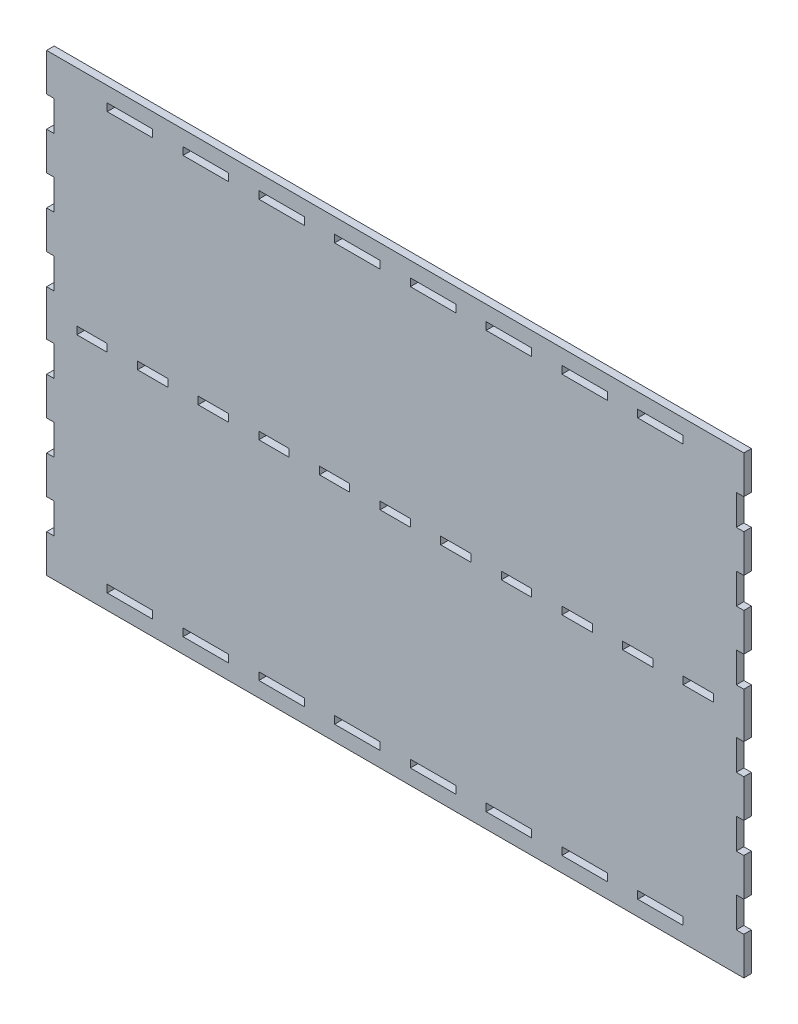
SolidWorks part; units mm, degrees
ref_plane "Front Plane" through (0, 0, 0) normal (0, 0, 1) x (1, 0, 0)
ref_plane "Top Plane" through (0, 0, 0) normal (0, 1, 0) x (1, 0, 0)
ref_plane "Right Plane" through (0, 0, 0) normal (1, 0, 0) x (0, 0, -1)
sketch "Sketch1" plane through (0, 0, 0) normal (0, 0, 1) x (1, 0, 0)
  line L0 (-145.2465, -150.1691) -> (-145.2465, -112.8993) construction
  line L1 (84.7535, -219.7844) -> (-375.2465, -219.7844)
  line L2 (84.7535, -219.7844) -> (84.7535, -194.7844)
  line L3 (84.7535, 80.2156) -> (-375.2465, 80.2156)
  line L4 (-375.2465, -219.7844) -> (-375.2465, -194.7844)
  line L5 (-118.9898, -69.7844) -> (-123.7326, -69.7844) construction
  line L6 (-55.2465, -204.7844) -> (-85.2465, -204.7844)
  line L7 (-105.2465, -209.7844) -> (-135.2465, -209.7844)
  line L8 (-105.2465, -209.7844) -> (-105.2465, -204.7844)
  line L9 (-105.2465, -204.7844) -> (-135.2465, -204.7844)
  line L10 (-135.2465, -209.7844) -> (-135.2465, -204.7844)
  line L11 (-85.2465, -209.7844) -> (-85.2465, -204.7844)
  line L12 (-55.2465, -209.7844) -> (-85.2465, -209.7844)
  line L13 (-55.2465, -209.7844) -> (-55.2465, -204.7844)
  line L14 (-5.2465, -204.7844) -> (-35.2465, -204.7844)
  line L15 (-35.2465, -209.7844) -> (-35.2465, -204.7844)
  line L16 (-5.2465, -209.7844) -> (-35.2465, -209.7844)
  line L17 (-5.2465, -209.7844) -> (-5.2465, -204.7844)
  line L18 (44.7535, -204.7844) -> (14.7535, -204.7844)
  line L19 (14.7535, -209.7844) -> (14.7535, -204.7844)
  line L20 (44.7535, -209.7844) -> (14.7535, -209.7844)
  line L21 (44.7535, -209.7844) -> (44.7535, -204.7844)
  line L22 (-335.2465, -209.7844) -> (-335.2465, -204.7844)
  line L23 (-335.2465, -209.7844) -> (-305.2465, -209.7844)
  line L24 (-305.2465, -209.7844) -> (-305.2465, -204.7844)
  line L25 (-335.2465, -204.7844) -> (-305.2465, -204.7844)
  line L26 (-285.2465, -209.7844) -> (-285.2465, -204.7844)
  line L27 (-285.2465, -209.7844) -> (-255.2465, -209.7844)
  line L28 (-255.2465, -209.7844) -> (-255.2465, -204.7844)
  line L29 (-285.2465, -204.7844) -> (-255.2465, -204.7844)
  line L30 (-235.2465, -209.7844) -> (-235.2465, -204.7844)
  line L31 (-235.2465, -209.7844) -> (-205.2465, -209.7844)
  line L32 (-205.2465, -209.7844) -> (-205.2465, -204.7844)
  line L33 (-155.2465, -209.7844) -> (-155.2465, -204.7844)
  line L34 (-185.2465, -204.7844) -> (-155.2465, -204.7844)
  line L35 (-185.2465, -209.7844) -> (-185.2465, -204.7844)
  line L36 (-185.2465, -209.7844) -> (-155.2465, -209.7844)
  line L37 (-235.2465, -204.7844) -> (-205.2465, -204.7844)
  line L38 (-235.2465, 65.2156) -> (-205.2465, 65.2156)
  line L39 (-185.2465, 70.2156) -> (-155.2465, 70.2156)
  line L40 (-185.2465, 70.2156) -> (-185.2465, 65.2156)
  line L41 (-185.2465, 65.2156) -> (-155.2465, 65.2156)
  line L42 (-155.2465, 70.2156) -> (-155.2465, 65.2156)
  line L43 (-205.2465, 70.2156) -> (-205.2465, 65.2156)
  line L44 (-235.2465, 70.2156) -> (-205.2465, 70.2156)
  line L45 (-235.2465, 70.2156) -> (-235.2465, 65.2156)
  line L46 (-285.2465, 65.2156) -> (-255.2465, 65.2156)
  line L47 (-255.2465, 70.2156) -> (-255.2465, 65.2156)
  line L48 (-285.2465, 70.2156) -> (-255.2465, 70.2156)
  line L49 (-285.2465, 70.2156) -> (-285.2465, 65.2156)
  line L50 (-335.2465, 65.2156) -> (-305.2465, 65.2156)
  line L51 (-305.2465, 70.2156) -> (-305.2465, 65.2156)
  line L52 (-335.2465, 70.2156) -> (-305.2465, 70.2156)
  line L53 (-335.2465, 70.2156) -> (-335.2465, 65.2156)
  line L54 (44.7535, 70.2156) -> (44.7535, 65.2156)
  line L55 (44.7535, 70.2156) -> (14.7535, 70.2156)
  line L56 (14.7535, 70.2156) -> (14.7535, 65.2156)
  line L57 (44.7535, 65.2156) -> (14.7535, 65.2156)
  line L58 (-5.2465, 70.2156) -> (-5.2465, 65.2156)
  line L59 (-5.2465, 70.2156) -> (-35.2465, 70.2156)
  line L60 (-35.2465, 70.2156) -> (-35.2465, 65.2156)
  line L61 (-5.2465, 65.2156) -> (-35.2465, 65.2156)
  line L62 (-55.2465, 70.2156) -> (-55.2465, 65.2156)
  line L63 (-55.2465, 70.2156) -> (-85.2465, 70.2156)
  line L64 (-85.2465, 70.2156) -> (-85.2465, 65.2156)
  line L65 (-135.2465, 70.2156) -> (-135.2465, 65.2156)
  line L66 (-105.2465, 65.2156) -> (-135.2465, 65.2156)
  line L67 (-105.2465, 70.2156) -> (-105.2465, 65.2156)
  line L68 (-105.2465, 70.2156) -> (-135.2465, 70.2156)
  line L69 (-55.2465, 65.2156) -> (-85.2465, 65.2156)
  line L70 (79.7535, 10.2156) -> (84.7535, 10.2156)
  line L71 (79.7535, -34.7844) -> (84.7535, -34.7844)
  line L72 (79.7535, -34.7844) -> (79.7535, -54.7844)
  line L73 (79.7535, -54.7844) -> (84.7535, -54.7844)
  line L76 (79.7535, 10.2156) -> (79.7535, -9.7844)
  line L77 (79.7535, -9.7844) -> (84.7535, -9.7844)
  line L78 (79.7535, 55.2156) -> (84.7535, 55.2156)
  line L80 (79.7535, 55.2156) -> (79.7535, 35.2156)
  line L81 (79.7535, 35.2156) -> (84.7535, 35.2156)
  line L82 (79.7535, -174.7844) -> (84.7535, -174.7844)
  line L83 (79.7535, -194.7844) -> (79.7535, -174.7844)
  line L85 (79.7535, -194.7844) -> (84.7535, -194.7844)
  line L86 (79.7535, -129.7844) -> (84.7535, -129.7844)
  line L87 (79.7535, -149.7844) -> (79.7535, -129.7844)
  line L90 (79.7535, -84.7844) -> (84.7535, -84.7844)
  line L91 (79.7535, -104.7844) -> (79.7535, -84.7844)
  line L92 (79.7535, -104.7844) -> (84.7535, -104.7844)
  line L93 (79.7535, -149.7844) -> (84.7535, -149.7844)
  line L94 (-370.2465, -149.7844) -> (-375.2465, -149.7844)
  line L95 (-370.2465, -104.7844) -> (-375.2465, -104.7844)
  line L96 (-370.2465, -104.7844) -> (-370.2465, -84.7844)
  line L97 (-370.2465, -84.7844) -> (-375.2465, -84.7844)
  line L100 (-370.2465, -149.7844) -> (-370.2465, -129.7844)
  line L101 (-370.2465, -129.7844) -> (-375.2465, -129.7844)
  line L102 (-370.2465, -194.7844) -> (-375.2465, -194.7844)
  line L104 (-370.2465, -194.7844) -> (-370.2465, -174.7844)
  line L105 (-370.2465, -174.7844) -> (-375.2465, -174.7844)
  line L106 (-370.2465, 35.2156) -> (-375.2465, 35.2156)
  line L107 (-370.2465, 55.2156) -> (-370.2465, 35.2156)
  line L109 (-370.2465, 55.2156) -> (-375.2465, 55.2156)
  line L110 (-370.2465, -9.7844) -> (-375.2465, -9.7844)
  line L111 (-370.2465, 10.2156) -> (-370.2465, -9.7844)
  line L114 (-370.2465, -54.7844) -> (-375.2465, -54.7844)
  line L115 (-370.2465, -34.7844) -> (-370.2465, -54.7844)
  line L116 (-370.2465, -34.7844) -> (-375.2465, -34.7844)
  line L117 (-370.2465, 10.2156) -> (-375.2465, 10.2156)
  line L118 (84.7535, -34.7844) -> (84.7535, -9.7844)
  line L119 (84.7535, 10.2156) -> (84.7535, 35.2156)
  line L120 (84.7535, 55.2156) -> (84.7535, 80.2156)
  line L121 (84.7535, -174.7844) -> (84.7535, -149.7844)
  line L122 (84.7535, -129.7844) -> (84.7535, -104.7844)
  line L123 (84.7535, -84.7844) -> (84.7535, -54.7844)
  line L124 (-375.2465, 55.2156) -> (-375.2465, 80.2156)
  line L125 (-375.2465, 10.2156) -> (-375.2465, 35.2156)
  line L126 (-375.2465, -34.7844) -> (-375.2465, -9.7844)
  line L127 (-375.2465, -84.7844) -> (-375.2465, -54.7844)
  line L128 (-375.2465, -129.7844) -> (-375.2465, -104.7844)
  line L129 (-375.2465, -174.7844) -> (-375.2465, -149.7844)
  line L130 (-195.2465, -67.2844) -> (-175.2465, -67.2844)
  line L131 (-155.2465, -67.2844) -> (-135.2465, -67.2844)
  line L132 (-155.2465, -67.2844) -> (-155.2465, -72.2844)
  line L133 (-155.2465, -72.2844) -> (-135.2465, -72.2844)
  line L134 (-135.2465, -67.2844) -> (-135.2465, -72.2844)
  line L135 (-155.2465, -67.2844) -> (-135.2465, -72.2844) construction
  line L136 (-155.2465, -72.2844) -> (-135.2465, -67.2844) construction
  line L137 (-195.2465, -67.2844) -> (-195.2465, -72.2844)
  line L138 (-195.2465, -72.2844) -> (-175.2465, -72.2844)
  line L139 (-175.2465, -67.2844) -> (-175.2465, -72.2844)
  line L140 (-235.2465, -67.2844) -> (-215.2465, -67.2844)
  line L141 (-235.2465, -67.2844) -> (-235.2465, -72.2844)
  line L142 (-235.2465, -72.2844) -> (-215.2465, -72.2844)
  line L143 (-215.2465, -67.2844) -> (-215.2465, -72.2844)
  line L144 (-275.2465, -67.2844) -> (-255.2465, -67.2844)
  line L145 (-275.2465, -67.2844) -> (-275.2465, -72.2844)
  line L146 (-275.2465, -72.2844) -> (-255.2465, -72.2844)
  line L147 (-255.2465, -67.2844) -> (-255.2465, -72.2844)
  line L148 (-315.2465, -67.2844) -> (-295.2465, -67.2844)
  line L149 (-315.2465, -67.2844) -> (-315.2465, -72.2844)
  line L150 (-315.2465, -72.2844) -> (-295.2465, -72.2844)
  line L151 (-295.2465, -67.2844) -> (-295.2465, -72.2844)
  line L152 (-355.2465, -67.2844) -> (-335.2465, -67.2844)
  line L153 (-355.2465, -67.2844) -> (-355.2465, -72.2844)
  line L154 (-355.2465, -72.2844) -> (-335.2465, -72.2844)
  line L155 (-335.2465, -67.2844) -> (-335.2465, -72.2844)
  line L276 (44.7535, -67.2844) -> (44.7535, -72.2844)
  line L277 (64.7535, -72.2844) -> (44.7535, -72.2844)
  line L278 (64.7535, -67.2844) -> (64.7535, -72.2844)
  line L279 (64.7535, -67.2844) -> (44.7535, -67.2844)
  line L280 (4.7535, -67.2844) -> (4.7535, -72.2844)
  line L281 (24.7535, -72.2844) -> (4.7535, -72.2844)
  line L282 (24.7535, -67.2844) -> (24.7535, -72.2844)
  line L283 (24.7535, -67.2844) -> (4.7535, -67.2844)
  line L284 (-35.2465, -67.2844) -> (-35.2465, -72.2844)
  line L285 (-15.2465, -72.2844) -> (-35.2465, -72.2844)
  line L286 (-15.2465, -67.2844) -> (-15.2465, -72.2844)
  line L287 (-15.2465, -67.2844) -> (-35.2465, -67.2844)
  line L288 (-75.2465, -67.2844) -> (-75.2465, -72.2844)
  line L289 (-55.2465, -72.2844) -> (-75.2465, -72.2844)
  line L290 (-55.2465, -67.2844) -> (-55.2465, -72.2844)
  line L291 (-55.2465, -67.2844) -> (-75.2465, -67.2844)
  line L292 (-115.2465, -67.2844) -> (-115.2465, -72.2844)
  line L293 (-95.2465, -72.2844) -> (-115.2465, -72.2844)
  line L294 (-95.2465, -67.2844) -> (-95.2465, -72.2844)
  line L295 (-95.2465, -67.2844) -> (-115.2465, -67.2844)
  point P120 (-145.2465, -69.7844)
  dimension "D1" = 150
  dimension "D2" = 150
  dimension "D3" = 5
  dimension "D4" = 230
  dimension "D5" = 5
  dimension "D6" = 30
  dimension "D7" = 10
  dimension "D9" = 10
  dimension "D10" = 20
  dimension "D11" = 5
  dimension "D12" = 20
  dimension "D13" = 20
  dimension "D14" = 15
  dimension "D16" = 25
  dimension "D19" = 20
  dimension "D8" = 4
  dimension "D15" = 3
  dimension "D17" = 6
  dimension "D18" = 1
extrude "Boss-Extrude1" add sketch "Sketch1" along normal blind 5
